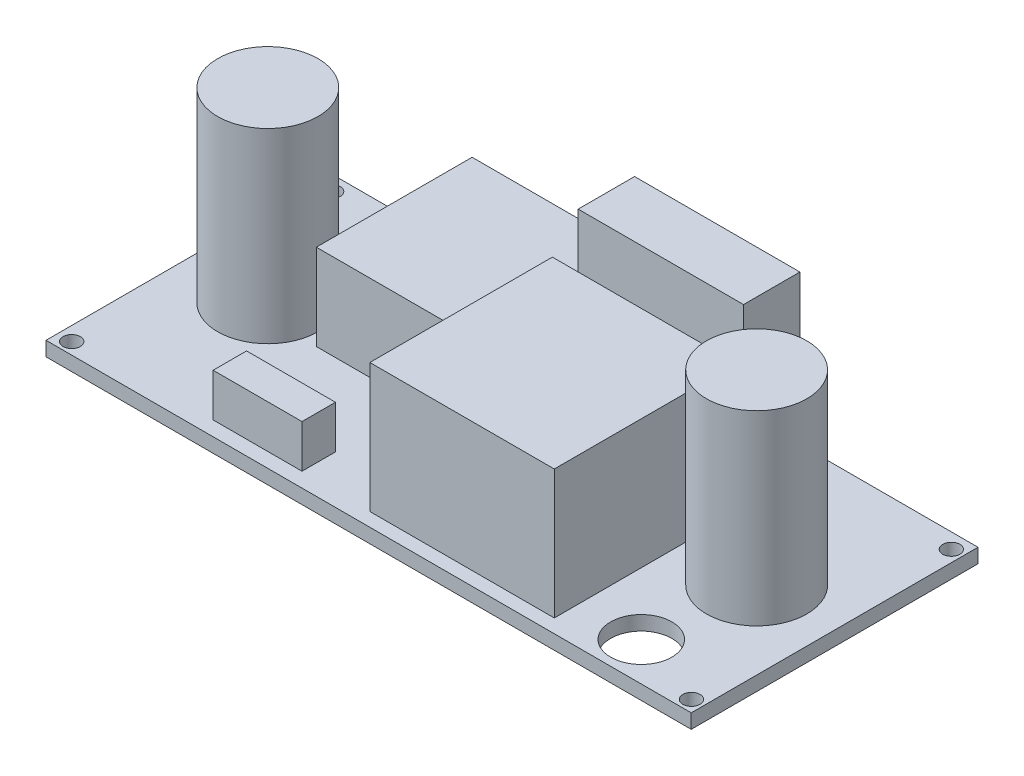
SolidWorks part; units mm, degrees
ref_plane "Front Plane" through (0, 0, 0) normal (0, 0, 1) x (1, 0, 0)
ref_plane "Top Plane" through (0, 0, 0) normal (0, 1, 0) x (1, 0, 0)
ref_plane "Right Plane" through (0, 0, 0) normal (1, 0, 0) x (0, 0, -1)
sketch "Sketch1" plane through (0, 0, 0) normal (0, 1, 0) x (1, 0, 0)
  line L1 (-22.5, 10) -> (22.5, 10)
  line L2 (-22.5, 10) -> (-22.5, -10)
  line L3 (-22.5, -10) -> (22.5, -10)
  line L4 (22.5, 10) -> (22.5, -10)
  line L5 (-22.5, 10) -> (22.5, -10) construction
  line L6 (-22.5, -10) -> (22.5, 10) construction
  dimension "D1" = 45
  dimension "D2" = 20
extrude "Boss-Extrude1" add sketch "Sketch1" along normal blind 1 contours L1 L4 L3 L2
sketch "Sketch2" plane through (0, 1, 0) normal (0, 1, 0) x (1, 0, 0)
  circle A0 centre (-17.0292, 0) radius 3.5
  circle A1 centre (17.0625, 0) radius 3.5
  point P19 (4.0657, -3.0493)
  point P20 (-8.1313, 4.8821)
  point P21 (3.2659, 6.9816)
  point P22 (6.5984, -3.0493)
  point P23 (0, 0)
  point P24 (0, 0)
extrude "Boss-Extrude3" add sketch "Sketch2" along normal blind 13
sketch "Sketch3" plane through (0, 1, 0) normal (0, 1, 0) x (1, 0, 0)
  line L1 (-0.8665, 9.4144) -> (10.6641, 9.4144)
  line L2 (-0.8665, 9.4144) -> (-0.8665, 5.482)
  line L3 (-0.8665, 5.482) -> (10.6641, 5.482)
  line L4 (10.6641, 9.4144) -> (10.6641, 5.482)
  line L5 (-0.8665, 9.4144) -> (10.6641, 5.482) construction
  line L6 (-0.8665, 5.482) -> (10.6641, 9.4144) construction
  point P0 (4.8988, 7.4482)
  point P5 (4.8988, 6.2485)
extrude "Boss-Extrude4" add sketch "Sketch3" along normal blind 11 contours L1 L4 L3 L2
sketch "Sketch4" plane through (0, 1, 0) normal (0, 1, 0) x (1, 0, 0)
  line L1 (-12.6969, 9.9142) -> (-2.0662, 9.9142)
  line L2 (-12.6969, 9.9142) -> (-12.6969, -0.9498)
  line L3 (-12.6969, -0.9498) -> (-2.0662, -0.9498)
  line L4 (-2.0662, 9.9142) -> (-2.0662, -0.9498)
  line L5 (-12.6969, 9.9142) -> (-2.0662, -0.9498) construction
  line L6 (-12.6969, -0.9498) -> (-2.0662, 9.9142) construction
  line L7 (-0.8665, 3.6824) -> (11.9971, 3.6824)
  line L8 (-0.8665, 3.6824) -> (-0.8665, -9.0478)
  line L9 (-0.8665, -9.0478) -> (11.9971, -9.0478)
  line L10 (11.9971, 3.6824) -> (11.9971, -9.0478)
  line L11 (-0.8665, 3.6824) -> (11.9971, -9.0478) construction
  line L12 (-0.8665, -9.0478) -> (11.9971, 3.6824) construction
  point P0 (-7.3815, 4.4822)
  point P5 (5.5653, -2.6827)
  point P10 (-7.7981, 5.3487)
extrude "Boss-Extrude5" add sketch "Sketch4" along normal blind 6
sketch "Sketch5" plane through (0, 7, 0) normal (0, 1, 0) x (1, 0, 0)
  line L0 (-0.8665, 3.6824) -> (11.9971, 3.6824)
  line L1 (11.9971, 3.6824) -> (11.9971, -9.0478)
  line L2 (11.9971, -9.0478) -> (-0.8665, -9.0478)
  line L3 (-0.8665, -9.0478) -> (-0.8665, 3.6824)
extrude "Boss-Extrude6" add sketch "Sketch5" along normal blind 3
sketch "Sketch6" plane through (0, 1, 0) normal (0, 1, 0) x (1, 0, 0)
  line L1 (-11.8638, -6.6484) -> (-5.6653, -6.6484)
  line L2 (-11.8638, -6.6484) -> (-11.8638, -8.9811)
  line L3 (-11.8638, -8.9811) -> (-5.6653, -8.9811)
  line L4 (-5.6653, -6.6484) -> (-5.6653, -8.9811)
  line L5 (-11.8638, -6.6484) -> (-5.6653, -8.9811) construction
  line L6 (-11.8638, -8.9811) -> (-5.6653, -6.6484) construction
  point P0 (-8.7645, -7.8148)
extrude "Boss-Extrude7" add sketch "Sketch6" along normal blind 3
sketch "Sketch7" plane through (0, 1, 0) normal (0, 1, 0) x (1, 0, 0)
  circle A0 centre (-21.5281, 8.9478) radius 0.6
  circle A1 centre (-21.5281, -9.1811) radius 0.6
  circle A2 centre (21.6947, -9.1811) radius 0.6
  circle A3 centre (21.6947, 8.9478) radius 0.6
  circle A4 centre (16.3293, -7.3149) radius 2.1339
  point P4 (16.3293, -7.3149)
extrude "Cut-Extrude1" cut sketch "Sketch7" against normal through all
